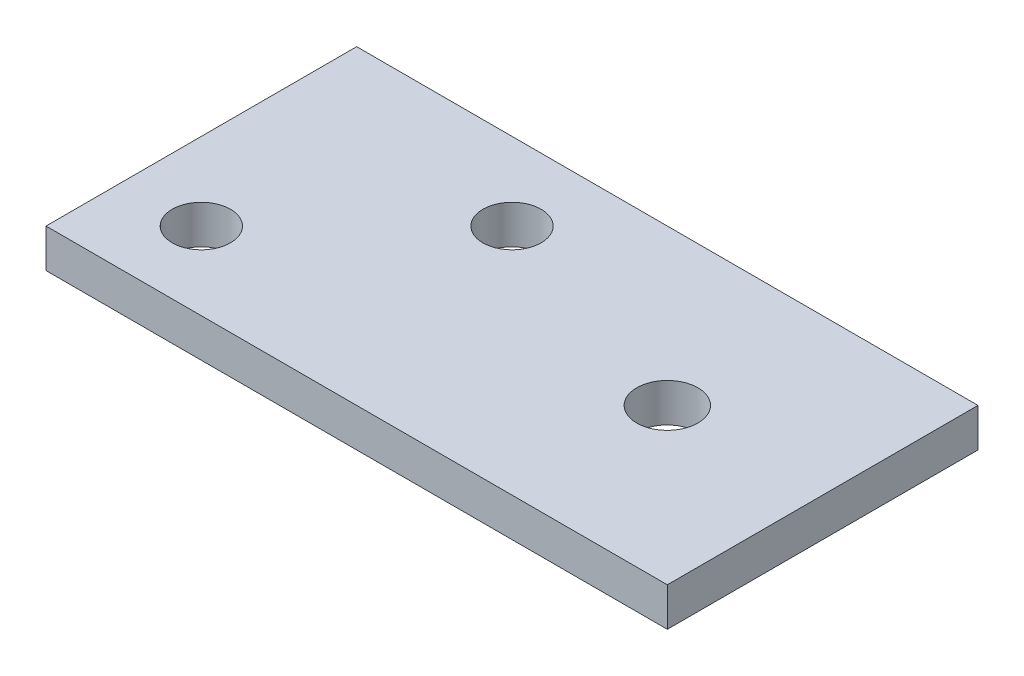
SolidWorks part; units mm, degrees
ref_plane "Alzado" through (0, 0, 0) normal (0, 0, 1) x (1, 0, 0)
ref_plane "Planta" through (0, 0, 0) normal (0, 1, 0) x (1, 0, 0)
ref_plane "Vista lateral" through (0, 0, 0) normal (1, 0, 0) x (0, 0, -1)
sketch "Croquis1" plane through (0, 0, 0) normal (0, 1, 0) x (1, 0, 0)
  line L1 (-50.8, 25.4) -> (50.8, 25.4)
  line L2 (-50.8, 25.4) -> (-50.8, -25.4)
  line L3 (-50.8, -25.4) -> (50.8, -25.4)
  line L4 (50.8, 25.4) -> (50.8, -25.4)
  line L5 (-50.8, 25.4) -> (50.8, -25.4) construction
  line L6 (-50.8, -25.4) -> (50.8, 25.4) construction
  point P0 (0, 0)
  dimension "D1" = 101.6
  dimension "D2" = 50.8
extrude "Saliente-Extruir1" add sketch "Croquis1" along normal blind 6.31
sketch "Croquis2" plane through (0, 6.31, 0) normal (0, 1, 0) x (1, 0, 0)
  line L0 (-50.8, 0) -> (50.8, 0) construction
  line L1 (-50.8, 25.4) -> (-50.8, -25.4) construction
  line L2 (50.8, -25.4) -> (50.8, 25.4) construction
  line L3 (50.8, 0) -> (0, 0) construction
  line L4 (0, 0) -> (25.4, 0) construction
  line L5 (25.4, 0) -> (25.4, 7.5763) construction
  line L6 (0, 0) -> (-50.8, 0) construction
  line L7 (-50.8, 0) -> (-25.4, 0) construction
  line L8 (-25.4, 0) -> (-25.4, 7.5763) construction
  line L9 (-25.4, 7.5763) -> (-18.1136, 12.9756) construction
  line L10 (-25.4, 0) -> (-50.8, -25.4) construction
  line L11 (-50.8, -25.4) -> (-25.4, 0) construction
  line L12 (0, 0) -> (0, 25.4) construction
  line L13 (50.8, 25.4) -> (-50.8, 25.4) construction
  line L14 (-25.4, 0) -> (-38.1, -12.7) construction
  line L15 (-38.1, -12.7) -> (-27.7316, -12.7) construction
  line L16 (-25.4, 0) -> (0, 25.4) construction
  line L17 (0, 25.4) -> (-12.7, 12.7) construction
  line L18 (-12.7, 12.7) -> (-7.8781, 12.7) construction
  circle A0 centre (-38.1, -12.7) radius 4.7625
  circle A1 centre (-12.7, 12.7) radius 4.7625
  dimension "D2" = 9.525
  dimension "D3" = 9.525
  dimension "D1" = 45
extrude "Cortar-Extruir1" cut sketch "Croquis2" against normal blind 6.31
sketch "Croquis3" plane through (0, 6.31, 0) normal (0, 1, 0) x (1, 0, 0)
  line L0 (17.118, 9.0161) -> (25.4, 0) construction
  line L1 (25.4, 0) -> (25.4, 4.765) construction
  circle A0 centre (25.4, 0) radius 4.765 construction
  circle A1 centre (25.4, 0) radius 5
  dimension "D1" = 10
extrude "Cortar-Extruir2" cut sketch "Croquis3" against normal blind 10
